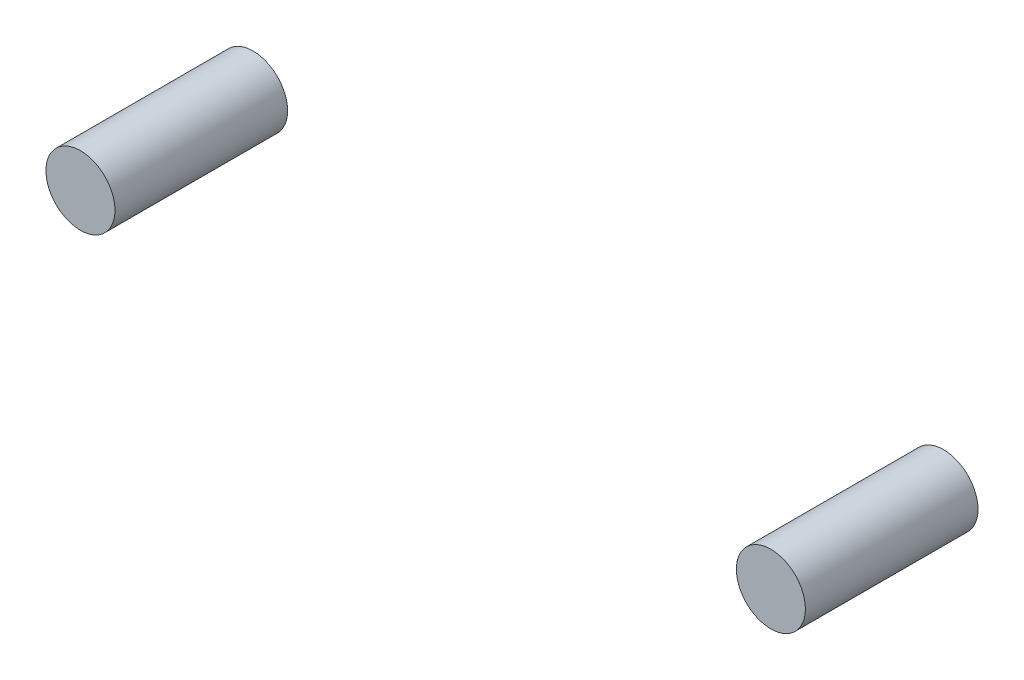
SolidWorks part; units mm, degrees
ref_plane "前视基准面" through (0, 0, 0) normal (0, 0, 1) x (1, 0, 0)
ref_plane "上视基准面" through (0, 0, 0) normal (0, 1, 0) x (1, 0, 0)
ref_plane "右视基准面" through (0, 0, 0) normal (1, 0, 0) x (0, 0, -1)
other "Configuration Table"
sketch "草图1" plane through (0, 0, 0) normal (0, 0, 1) x (1, 0, 0)
  line L0 (-8.8616, 0) -> (11.1384, 0) construction
  circle A0 centre (-8.8616, 0) radius 1
  circle A1 centre (11.1384, 0) radius 1
  dimension "D1" = 20
extrude "凸台-拉伸1" add sketch "草图1" along normal blind 5
